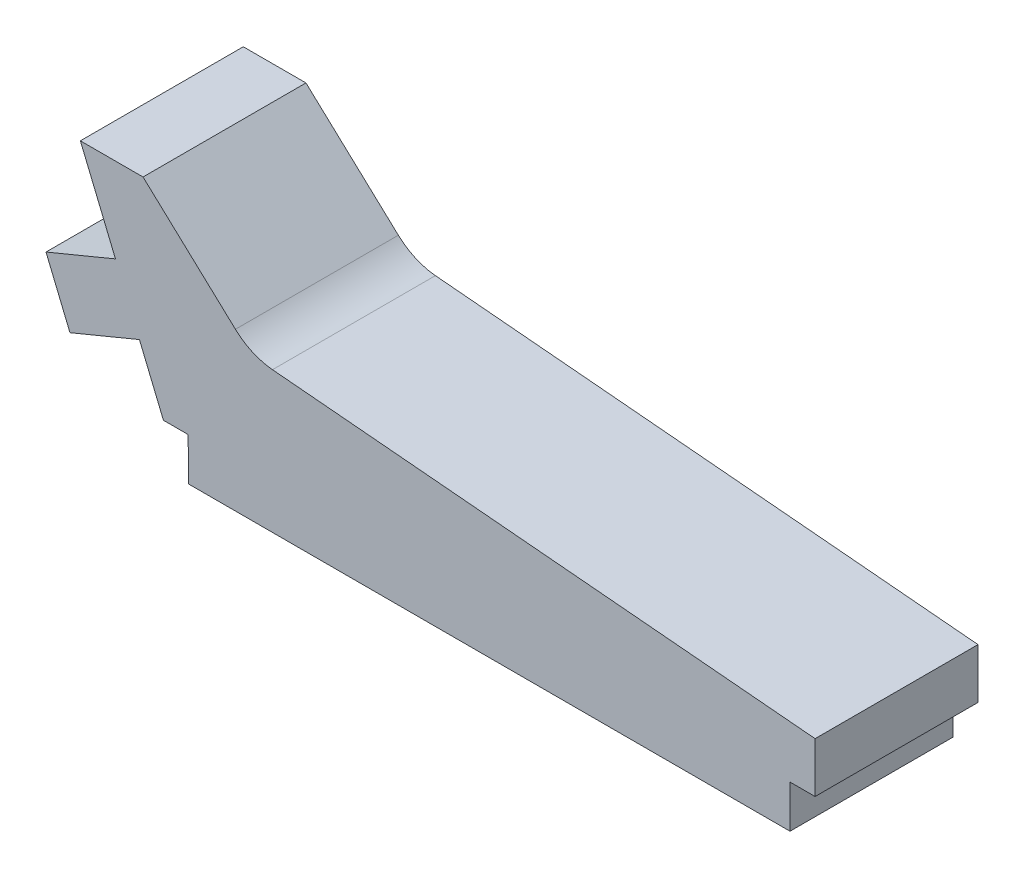
SolidWorks part; units mm, degrees
ref_plane "Plane1" through (0, 0, 0) normal (0, 0, 1) x (1, 0, 0)
ref_plane "Plane2" through (0, 0, 0) normal (0, 1, 0) x (1, 0, 0)
ref_plane "Plane3" through (0, 0, 0) normal (1, 0, 0) x (0, 0, -1)
sketch "Sketch1" plane through (0, 0, 0) normal (0, 0, 1) x (1, 0, 0)
  line L1 (0, 0) -> (203.2, 0)
  line L2 (0, 0) -> (0, 101.6)
  line L3 (0, 101.6) -> (203.2, 101.6)
  line L4 (203.2, 0) -> (203.2, 101.6)
  dimension "D1" = 203.2
  dimension "D2" = 101.6
extrude "Extrude1" add sketch "Sketch1" along normal blind 50.8
sketch "Sketch2" plane through (0, 0, 50.8) normal (0, 0, 1) x (1, 0, 0)
  line L0 (83.0232, 99.06) -> (89.3732, 99.06)
  line L2 (157.48, 83.82) -> (157.48, 78.74)
  line L3 (157.48, 78.74) -> (91.44, 78.74)
  line L4 (91.44, 78.74) -> (83.0232, 99.06)
  line L5 (203.2, 101.6) -> (0, 101.6) construction
  line L6 (0, 101.6) -> (0, 0) construction
  line L7 (157.48, 83.82) -> (102.4931, 88.7077)
  line L8 (98.7377, 90.3765) -> (89.3732, 99.06)
  arc A0 (98.7377, 90.3765) -> (102.4931, 88.7077) centre (103.0553, 95.0328) ccw
  point P12 (100.33, 88.9)
  dimension "D10" = 6.35
  dimension "D1" = 67.5
  dimension "D2" = 20.32
  dimension "D3" = 2.54
  dimension "D4" = 5.08
  dimension "D5" = 66.04
  dimension "D6" = 157.48
  dimension "D7" = 6.35
  dimension "D8" = 57.15
  dimension "D9" = 5.08
sketch "Sketch4" plane through (0, 0, 50.8) normal (0, 0, 1) x (1, 0, 0)
  line L0 (86.5799, 90.4733) -> (72.5, 84.6412)
  line L1 (91.44, 78.74) -> (83.0232, 99.06) construction
  line L2 (72.5, 84.6412) -> (69.6673, 84.8425)
  line L3 (69.6673, 84.8425) -> (73.0694, 76.6292)
  line L4 (73.0694, 76.6292) -> (74.93, 78.7745)
  line L5 (74.93, 78.7745) -> (89.01, 84.6066)
  line L6 (89.01, 84.6066) -> (91.8426, 84.4053)
  line L7 (91.8426, 84.4053) -> (88.4406, 92.6186)
  line L8 (88.4406, 92.6186) -> (86.5799, 90.4733)
  line L9 (79.54, 87.5572) -> (81.97, 81.6906)
  dimension "D1" = 6.35
  dimension "D2" = 8.89
  dimension "D3" = 1.27
  dimension "D4" = 8.89
  dimension "D5" = 1.27
  dimension "D6" = 2.54
  dimension "D7" = 2.54
  dimension "D8" = 15.24
  dimension "D9" = 6.35
sketch "Sketch5" plane through (0, 0, 50.8) normal (0, 0, 1) x (1, 0, 0)
  line L0 (69.7842, 91.1978) -> (77.5603, 72.4245)
  line L1 (77.5603, 72.4245) -> (43.4353, 38.2996)
  line L2 (43.4353, 38.2996) -> (23.4233, 51.0486)
  line L5 (23.4233, 51.0486) -> (30.1436, 56.8684)
  line L6 (157.48, 78.74) -> (91.44, 78.74) construction
  line L7 (30.1436, 56.8684) -> (37.6275, 52.1007)
  line L8 (45.5295, 52.9661) -> (64.4212, 71.8578)
  line L9 (65.7977, 78.778) -> (63.0639, 85.3779)
  line L10 (63.0639, 85.3779) -> (69.7842, 91.1978)
  arc A0 (37.6275, 52.1007) -> (45.5295, 52.9661) centre (41.0393, 57.4562) ccw
  arc A1 (65.7977, 78.778) -> (64.4212, 71.8578) centre (59.9311, 76.3479) cw
  point P14 (41.9258, 49.3624)
  dimension "D10" = 6.35
  dimension "D1" = 135
  dimension "D2" = 6.35
  dimension "D3" = 8.89
  dimension "D4" = 48.26
  dimension "D5" = 102.5
  dimension "D6" = 8.89
  dimension "D7" = 20.32
  dimension "D8" = 8.89
  dimension "D9" = 13.97
sketch "Sketch6" plane through (0, 0, 50.8) normal (0, 0, 1) x (1, 0, 0)
  line L0 (31.6531, 45.8056) -> (23.4647, 32.9524)
  line L1 (43.4353, 38.2996) -> (23.4233, 51.0486) construction
  line L2 (23.4647, 32.9524) -> (21.0288, 31.4925)
  line L3 (21.0288, 31.4925) -> (26.3844, 28.0807)
  line L4 (26.3844, 28.0807) -> (26.678, 30.9052)
  line L5 (26.678, 30.9052) -> (34.8665, 43.7585)
  line L6 (34.8665, 43.7585) -> (37.3023, 45.2184)
  line L7 (37.3023, 45.2184) -> (31.9468, 48.6302)
  line L8 (30.7722, 37.3319) -> (27.5589, 39.379)
  line L9 (31.9468, 48.6302) -> (31.6531, 45.8056)
  dimension "D1" = 3.81
  dimension "D2" = 6.35
  dimension "D3" = 6.35
  dimension "D4" = 1.27
  dimension "D5" = 1.27
  dimension "D6" = 2.54
  dimension "D7" = 2.54
  dimension "D8" = 15.24
  dimension "D9" = 10.16
sketch "Sketch8" plane through (0, 0, 50.8) normal (0, 0, 1) x (1, 0, 0)
  line L0 (16.648, 37.2951) -> (33.1047, 26.811)
  line L1 (33.1047, 26.811) -> (26.5892, 8.9099)
  line L2 (26.5892, 8.9099) -> (2.721, 17.5972)
  line L3 (16.648, 37.2951) -> (10.6809, 39.4669)
  line L4 (2.721, 17.5972) -> (10.6809, 39.4669)
  line L8 (43.4353, 38.2996) -> (23.4233, 51.0486) construction
  dimension "D1" = 7.62
  dimension "D2" = 102.5
  dimension "D3" = 25.4
  dimension "D4" = 19.05
  dimension "D5" = 6.35
sketch "Sketch14" plane through (0, 0, 50.8) normal (0, 0, 1) x (1, 0, 0)
  line L0 (157.48, 78.74) -> (91.44, 78.74) construction
  line L1 (93.98, 80.772) -> (154.94, 80.772)
  line L2 (93.98, 80.772) -> (93.98, 74.422)
  line L3 (93.98, 74.422) -> (154.94, 74.422)
  line L4 (154.94, 80.772) -> (154.94, 74.422)
  line L5 (157.48, 83.82) -> (157.48, 78.74) construction
  dimension "D1" = 2.032
  dimension "D2" = 2.54
  dimension "D3" = 2.54
  dimension "D4" = 6.35
sketch "Sketch15" plane through (0, 0, 50.8) normal (0, 0, 1) x (1, 0, 0)
  line L0 (43.7945, 41.5325) -> (48.2847, 37.0423)
  line L2 (48.2847, 37.0423) -> (78.8175, 67.5752)
  line L3 (78.8175, 67.5752) -> (74.3274, 72.0653)
  line L4 (74.3274, 72.0653) -> (43.7945, 41.5325)
  line L5 (77.5603, 72.4245) -> (43.4353, 38.2996) construction
  dimension "D1" = 2.032
  dimension "D2" = 2.54
  dimension "D3" = 6.35
  dimension "D4" = 2.54
sketch "Sketch16" plane through (0, 0, 50.8) normal (0, 0, 1) x (1, 0, 0)
  line L0 (25.5485, 11.9917) -> (31.5155, 9.8199)
  line L1 (31.5155, 9.8199) -> (36.2935, 22.9474)
  line L2 (36.2935, 22.9474) -> (30.3265, 25.1192)
  line L3 (30.3265, 25.1192) -> (25.5485, 11.9917)
  line L4 (33.1047, 26.811) -> (26.5892, 8.9099) construction
  dimension "D1" = 2.032
  dimension "D2" = 6.35
  dimension "D3" = 2.54
  dimension "D4" = 2.54
sketch "Sketch19" plane through (0, 0, 50.8) normal (0, 0, 1) x (1, 0, 0)
  line L0 (155.194, 72.39) -> (86.506, 72.39)
  line L1 (86.506, 72.39) -> (45.2314, 31.1154)
  line L2 (45.2314, 31.1154) -> (113.9194, 31.1154)
  line L3 (113.9194, 31.1154) -> (155.194, 72.39)
  line L4 (93.98, 74.422) -> (154.94, 74.422) construction
  line L5 (48.2847, 37.0423) -> (78.8175, 67.5752) construction
  line L7 (43.7945, 41.5325) -> (48.2847, 37.0423) construction
  line L8 (154.94, 80.772) -> (154.94, 74.422) construction
  dimension "D1" = 2.032
  dimension "D2" = 2.032
  dimension "D3" = 6.35
  dimension "D4" = 0.254
sketch "Sketch20" plane through (0, 0, 50.8) normal (0, 0, 1) x (1, 0, 0)
  line L0 (79.54, 87.5572) -> (81.97, 81.6906)
  line L1 (81.97, 81.6906) -> (89.01, 84.6066)
  line L2 (89.01, 84.6066) -> (91.44, 78.74)
  line L3 (91.44, 78.74) -> (93.9474, 78.74)
  line L4 (93.9474, 78.74) -> (93.98, 74.422)
  line L5 (93.98, 74.422) -> (154.94, 74.422)
  line L6 (154.94, 74.422) -> (154.94, 78.74)
  line L7 (154.94, 78.74) -> (157.48, 78.74)
  line L8 (157.48, 78.74) -> (157.48, 83.82)
  line L9 (157.48, 83.82) -> (102.4931, 88.7077)
  line L10 (98.7377, 90.3765) -> (89.3732, 99.06)
  line L11 (89.3732, 99.06) -> (83.0232, 99.06)
  line L12 (83.0232, 99.06) -> (86.5799, 90.4733)
  line L13 (86.5799, 90.4733) -> (79.54, 87.5572)
  arc A0 (98.7377, 90.3765) -> (102.4931, 88.7077) centre (103.0553, 95.0328) ccw
extrude "Extrude2" add sketch "Sketch20" along normal blind 16.51 contours A0 L10 L11 L12 L13 L0 L1 L2 L3 L4 L5 L6 L7 L8 L9
sketch "Sketch22" plane through (0, 101.6, 0) normal (0, 1, 0) x (1, 0, 0)
  line L0 (203.2, -50.8) -> (203.2, 0)
  line L1 (203.2, 0) -> (0, 0) construction
  line L2 (203.2, -50.8) -> (203.2, 0) construction
  line L3 (203.2, 0) -> (0, 0)
  line L4 (0, 0) -> (0, -50.8)
  line L5 (0, -50.8) -> (203.2, -50.8)
extrude "Extrude3" cut sketch "Sketch22" against normal blind 12700
sketch "Sketch23" plane through (98.8478, 40.9441, 0) normal (-0.9239, -0.3827, 0) x (0, 0, 1)
  line L0 (67.31, 44.1037) -> (50.8, 44.1037) construction
  point P0 (59.055, 44.1037)
  point P1 (-10.1158, -42.7025)
